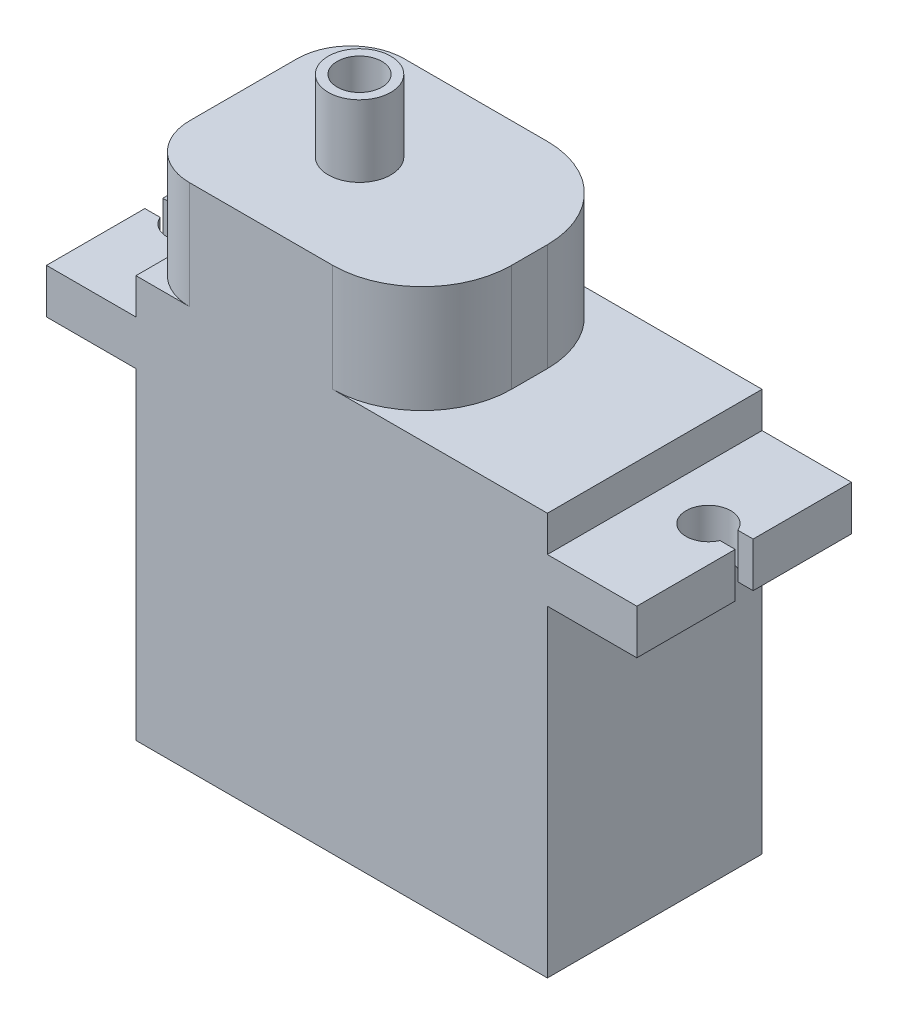
SolidWorks part; units mm, degrees
ref_plane "Front Plane" through (0, 0, 0) normal (0, 0, 1) x (1, 0, 0)
ref_plane "Top Plane" through (0, 0, 0) normal (0, 1, 0) x (1, 0, 0)
ref_plane "Right Plane" through (0, 0, 0) normal (1, 0, 0) x (0, 0, -1)
sketch "Sketch1" plane through (0, 0, 0) normal (0, 1, 0) x (1, 0, 0)
  line L1 (-11.5, 6) -> (11.5, 6)
  line L2 (-11.5, 6) -> (-11.5, -6)
  line L3 (-11.5, -6) -> (11.5, -6)
  line L4 (11.5, 6) -> (11.5, -6)
  line L5 (-11.5, 6) -> (11.5, -6) construction
  line L6 (-11.5, -6) -> (11.5, 6) construction
  point P0 (0, 0)
  dimension "D1" = 23
  dimension "D2" = 12
extrude "Boss-Extrude1" add sketch "Sketch1" along normal blind 22.5
sketch "Sketch2" plane through (11.5, 0, 0) normal (1, 0, 0) x (0, 0, -1)
  line L0 (-6, 22.5) -> (-6, 0) construction
  line L1 (-6, 20.5) -> (6, 20.5)
  line L2 (-6, 20.5) -> (-6, 18)
  line L3 (-6, 18) -> (6, 18)
  line L4 (6, 20.5) -> (6, 18)
  line L5 (6, 22.5) -> (6, 0) construction
  line L6 (-6, 0) -> (6, 0) construction
  dimension "D1" = 2.5
  dimension "D2" = 18
extrude "Boss-Extrude2" add sketch "Sketch2" along normal blind 5
sketch "Sketch3" plane through (0, 20.5, 0) normal (0, 1, 0) x (1, 0, 0)
  line L0 (16.5, 6) -> (16.5, -6) construction
  line L1 (15.6456, 0.5) -> (16.5, 0.5)
  line L2 (16.5, 0.5) -> (16.5, -0.5)
  line L3 (16.5, -0.5) -> (15.6456, -0.5)
  arc A0 (15.6456, 0.5) -> (15.6456, -0.5) centre (14.5, 0) ccw
  dimension "D1" = 2.5
  dimension "D2" = 2
  dimension "D3" = 1
extrude "Cut-Extrude1" cut sketch "Sketch3" against normal blind 5
mirror "Mirror1" about plane through (0, 0, 0) normal (1, 0, 0) of "Cut-Extrude1", "Boss-Extrude2"
sketch "Sketch4" plane through (0, 22.5, 0) normal (0, 1, 0) x (1, 0, 0)
  line L1 (-8.5, 6) -> (4.5, 6)
  line L2 (-11.5, 3) -> (-11.5, -3)
  line L3 (-8.5, -6) -> (4.5, -6)
  line L4 (4.5, 6) -> (4.5, -6)
  line L5 (-11.5, -6) -> (11.5, -6) construction
  arc A0 (-8.5, 6) -> (-11.5, 3) centre (-8.5, 3) ccw
  arc A1 (-11.5, -3) -> (-8.5, -6) centre (-8.5, -3) ccw
  point P10 (-11.5, 6)
  dimension "D2" = 3
  dimension "D1" = 16
extrude "Boss-Extrude3" add sketch "Sketch4" along normal blind 6
fillet "Fillet1" radius 5 2 edges at (4.5, 25.5, -6) (4.5, 25.5, 6)
sketch "Sketch5" plane through (0, 28.5, 0) normal (0, 1, 0) x (1, 0, 0)
  line L0 (-11.5, 6) -> (-11.5, -6) construction
  circle A0 centre (-5, 0) radius 1.75
  dimension "D1" = 3.5
  dimension "D2" = 6.5
extrude "Boss-Extrude4" add sketch "Sketch5" along normal blind 4
sketch "Sketch6" plane through (0, 32.5, 0) normal (0, 1, 0) x (1, 0, 0)
  circle A0 centre (-5, 0) radius 1.25
  dimension "D1" = 2.5
extrude "Cut-Extrude2" cut sketch "Sketch6" against normal blind 4
